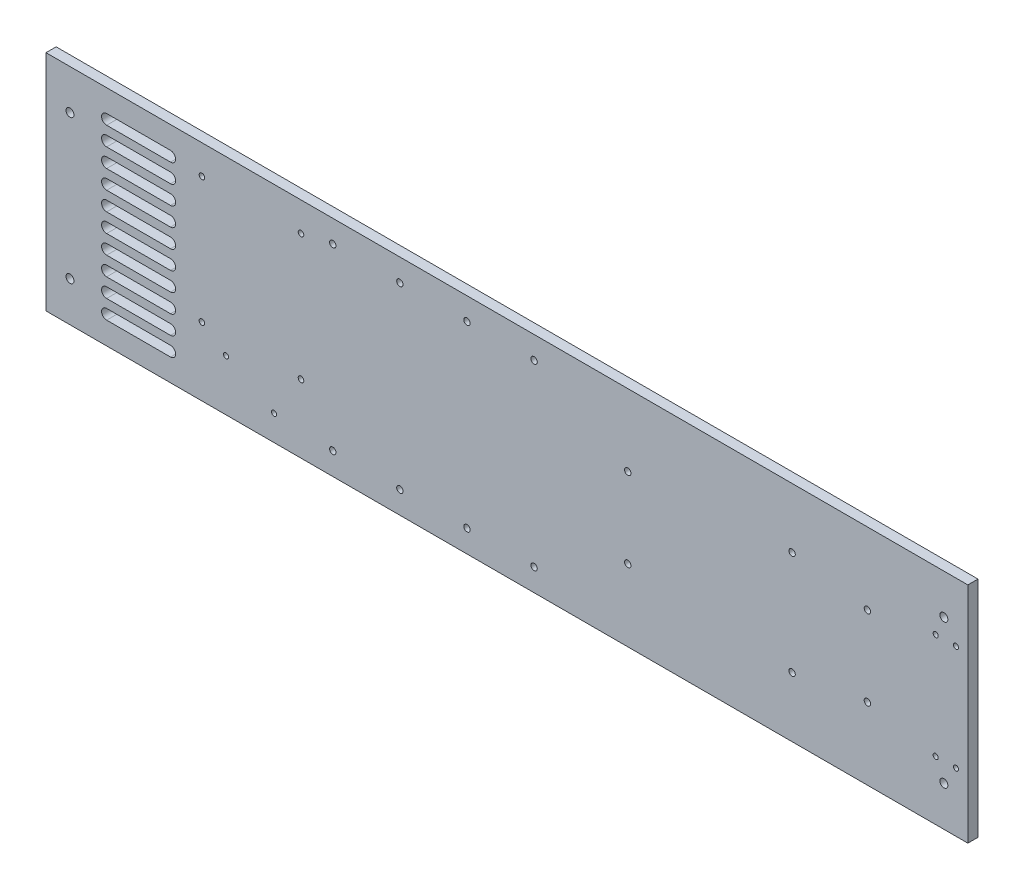
SolidWorks part; units mm, degrees
ref_plane "Front Plane" through (0, 0, 0) normal (0, 0, 1) x (1, 0, 0)
ref_plane "Top Plane" through (0, 0, 0) normal (0, 1, 0) x (1, 0, 0)
ref_plane "Right Plane" through (0, 0, 0) normal (1, 0, 0) x (0, 0, -1)
sketch "Sketch1" plane through (0, 0, 0) normal (0, 0, 1) x (1, 0, 0)
  line L1 (-288.5, 70) -> (288.5, 70)
  line L2 (-288.5, 70) -> (-288.5, -70)
  line L3 (-288.5, -70) -> (288.5, -70)
  line L4 (288.5, 70) -> (288.5, -70)
  line L5 (-288.5, 70) -> (288.5, -70) construction
  line L6 (-288.5, -70) -> (288.5, 70) construction
  point P0 (0, 0)
  dimension "D1" = 577
  dimension "D2" = 140
extrude "Boss-Extrude1" add sketch "Sketch1" along normal blind 6.35
sketch "Sketch2" plane through (0, 0, 6.35) normal (0, 0, 1) x (1, 0, 0)
  line L0 (43.12, 57.5) -> (43.12, -57.5) construction
  line L1 (43.12, -57.5) -> (258.12, -57.5) construction
  line L2 (258.12, -57.5) -> (258.12, 57.5) construction
  line L3 (258.12, 57.5) -> (43.12, 57.5) construction
  line L4 (150.62, 57.5) -> (150.62, -57.5) construction
  line L5 (150.62, -57.5) -> (150.62, 0) construction
  line L6 (150.62, 0) -> (43.12, 0) construction
  line L7 (43.12, 0) -> (258.12, 0) construction
  line L8 (4.9962, 58) -> (38.9962, 58) construction
  line L9 (38.9962, 58) -> (38.9962, -58) construction
  line L10 (38.9962, -58) -> (4.9962, -58) construction
  line L11 (4.9962, -58) -> (4.9962, 58) construction
  line L12 (16.9962, 58) -> (16.9962, -58) construction
  line L13 (38.9962, 0) -> (4.9962, 0) construction
  line L14 (-37.0038, 58) -> (-3.0038, 58) construction
  line L15 (-3.0038, 58) -> (-3.0038, -58) construction
  line L16 (-3.0038, -58) -> (-37.0038, -58) construction
  line L17 (-37.0038, -58) -> (-37.0038, 58) construction
  line L18 (-25.0038, 58) -> (-25.0038, -58) construction
  line L19 (-3.0038, 0) -> (-37.0038, 0) construction
  line L20 (-79.0038, 58) -> (-45.0038, 58) construction
  line L21 (-45.0038, 58) -> (-45.0038, -58) construction
  line L22 (-45.0038, -58) -> (-79.0038, -58) construction
  line L23 (-79.0038, -58) -> (-79.0038, 58) construction
  line L24 (-67.0038, 58) -> (-67.0038, -58) construction
  line L25 (-45.0038, 0) -> (-79.0038, 0) construction
  line L26 (-121.0038, 58) -> (-87.0038, 58) construction
  line L27 (-87.0038, 58) -> (-87.0038, -58) construction
  line L28 (-87.0038, -58) -> (-121.0038, -58) construction
  line L29 (-121.0038, -58) -> (-121.0038, 58) construction
  line L30 (-109.0038, 58) -> (-109.0038, -58) construction
  line L31 (-87.0038, 0) -> (-121.0038, 0) construction
  line L32 (-189.1559, 12.2683) -> (-130.6237, 12.2683) construction
  line L33 (-130.6237, 12.2683) -> (-159.8898, 12.2683) construction
  line L34 (-159.8898, 12.2683) -> (-159.8898, 43.5) construction
  line L35 (-159.8898, 43.5) -> (-159.8898, -43.5) construction
  line L36 (-194.8898, 55.7683) -> (-194.8898, -31.2317) construction
  line L37 (-194.8898, -31.2317) -> (-124.8898, -31.2317) construction
  line L38 (-124.8898, -31.2317) -> (-124.8898, 55.7683) construction
  line L39 (-124.8898, 55.7683) -> (-194.8898, 55.7683) construction
  line L40 (266.2213, 35.125) -> (266.2213, -35.125) construction
  line L41 (266.2213, -35.125) -> (283.2213, -35.125) construction
  line L42 (283.2213, -35.125) -> (283.2213, 35.125) construction
  line L43 (283.2213, 35.125) -> (266.2213, 35.125) construction
  line L44 (274.7213, 35.125) -> (274.7213, -35.125) construction
  line L45 (274.7213, -35.125) -> (274.7213, 0) construction
  line L46 (274.7213, 0) -> (283.2213, 0) construction
  line L47 (283.2213, 0) -> (266.2213, 0) construction
  line L48 (-182.4288, -35.379) -> (-139.1788, -35.379) construction
  line L49 (-139.1788, -35.379) -> (-139.1788, -56.629) construction
  line L50 (-139.1788, -56.629) -> (-182.4288, -56.629) construction
  line L51 (-182.4288, -56.629) -> (-182.4288, -35.379) construction
  line L52 (141.4817, 37) -> (215.4817, 37) construction
  line L53 (215.4817, 37) -> (215.4817, -37) construction
  line L54 (215.4817, -37) -> (141.4817, -37) construction
  line L55 (141.4817, -37) -> (141.4817, 37) construction
  line L56 (141.4817, 0) -> (215.4817, 0) construction
  line L57 (178.4817, 37) -> (178.4817, -37) construction
  circle A0 centre (75.62, 25) radius 2
  circle A1 centre (225.62, 25) radius 2
  circle A2 centre (225.62, -25) radius 2
  circle A3 centre (75.62, -25) radius 2
  circle A4 centre (16.9962, 56) radius 2
  circle A5 centre (16.9962, -56) radius 2
  circle A6 centre (-25.0038, 56) radius 2
  circle A7 centre (-25.0038, -56) radius 2
  circle A8 centre (-67.0038, 56) radius 2
  circle A9 centre (-67.0038, -56) radius 2
  circle A10 centre (-109.0038, 56) radius 2
  circle A11 centre (-109.0038, -56) radius 2
  circle A12 centre (-128.8898, 51.7683) radius 1.75
  circle A13 centre (-190.8898, 51.7683) radius 1.75
  circle A14 centre (-128.8898, -27.2317) radius 1.75
  circle A15 centre (-190.8898, -27.2317) radius 1.75
  circle A16 centre (268.3713, 33) radius 1.6
  circle A17 centre (281.0713, 33) radius 1.6
  circle A18 centre (281.0713, -33) radius 1.6
  circle A19 centre (268.3713, -33) radius 1.6
  circle A20 centre (-145.7788, -54.079) radius 1.5875
  circle A21 centre (-175.8288, -37.929) radius 1.5875
  circle A22 centre (178.4817, 32.5) radius 2
  circle A23 centre (178.4817, -32.5) radius 2
  point P19 (38.9962, 0)
  dimension "D3" = 75
  dimension "D4" = 4
  dimension "D5" = 25
  dimension "D6" = 34
  dimension "D9" = 4
  dimension "D10" = 56
  dimension "D12" = 3.5
  dimension "D13" = 39.5
  dimension "D14" = 31
  dimension "D15" = 4
  dimension "D17" = 4
  dimension "D18" = 4
  dimension "D21" = 3.2
  dimension "D22" = 6.35
  dimension "D23" = 33
  dimension "D27" = 3.175
  dimension "D28" = 3.175
  dimension "D29" = 2.55
  dimension "D30" = 2.55
  dimension "D31" = 6.6
  dimension "D32" = 6.6
  dimension "D35" = 32.5
  dimension "D36" = 4
  dimension "D1" = 215
  dimension "D2" = 115
  dimension "D7" = 116
  dimension "D8" = 22
  dimension "D16" = 4
  dimension "D19" = 70.25
  dimension "D20" = 17
  dimension "D24" = 8
  dimension "D25" = 43.25
  dimension "D26" = 21.25
  dimension "D33" = 74
  dimension "D34" = 74
  dimension "D11" = 4
extrude "Cut-Extrude1" cut sketch "Sketch2" against normal through all
sketch "Sketch4" plane through (0, 0, 6.35) normal (0, 0, 1) x (1, 0, 0)
  line L0 (288.5, 70) -> (-288.5, 70) construction
  line L1 (-288.5, 70) -> (-288.5, -70) construction
  line L2 (-73.8138, 0) -> (0, 0) construction
  line L3 (0, 0) -> (0, 94.1959) construction
  circle A0 centre (-273.5, 45) radius 2.5
  circle A1 centre (273.5, 45) radius 2.5
  circle A2 centre (273.5, -45) radius 2.5
  circle A3 centre (-273.5, -45) radius 2.5
  dimension "D1" = 5
  dimension "D2" = 25
  dimension "D3" = 15
extrude "Cut-Extrude2" cut sketch "Sketch4" against normal through all
sketch "Sketch5" plane through (0, 0, 6.35) normal (0, 0, 1) x (1, 0, 0)
  line L0 (-250.5462, 52.825) -> (-210.5462, 52.825) construction
  line L1 (-250.5462, 56) -> (-210.5462, 56)
  line L2 (-250.5462, 49.65) -> (-210.5462, 49.65)
  line L3 (-250.5462, 41.0861) -> (-210.5462, 41.0861) construction
  line L4 (-250.5462, 44.2611) -> (-210.5462, 44.2611)
  line L5 (-250.5462, 37.9111) -> (-210.5462, 37.9111)
  line L6 (-250.5462, 29.3472) -> (-210.5462, 29.3472) construction
  line L7 (-250.5462, 32.5222) -> (-210.5462, 32.5222)
  line L8 (-250.5462, 26.1722) -> (-210.5462, 26.1722)
  line L9 (-250.5462, 17.6083) -> (-210.5462, 17.6083) construction
  line L10 (-250.5462, 20.7833) -> (-210.5462, 20.7833)
  line L11 (-250.5462, 14.4333) -> (-210.5462, 14.4333)
  line L12 (-250.5462, 5.8694) -> (-210.5462, 5.8694) construction
  line L13 (-250.5462, 9.0444) -> (-210.5462, 9.0444)
  line L14 (-250.5462, 2.6944) -> (-210.5462, 2.6944)
  line L15 (-250.5462, -5.8694) -> (-210.5462, -5.8694) construction
  line L16 (-250.5462, -2.6944) -> (-210.5462, -2.6944)
  line L17 (-250.5462, -9.0444) -> (-210.5462, -9.0444)
  line L18 (-250.5462, -17.6083) -> (-210.5462, -17.6083) construction
  line L19 (-250.5462, -14.4333) -> (-210.5462, -14.4333)
  line L20 (-250.5462, -20.7833) -> (-210.5462, -20.7833)
  line L21 (-250.5462, -29.3472) -> (-210.5462, -29.3472) construction
  line L22 (-250.5462, -26.1722) -> (-210.5462, -26.1722)
  line L23 (-250.5462, -32.5222) -> (-210.5462, -32.5222)
  line L24 (-250.5462, -41.0861) -> (-210.5462, -41.0861) construction
  line L25 (-250.5462, -37.9111) -> (-210.5462, -37.9111)
  line L26 (-250.5462, -44.2611) -> (-210.5462, -44.2611)
  line L27 (-250.5462, -52.825) -> (-210.5462, -52.825) construction
  line L28 (-250.5462, -49.65) -> (-210.5462, -49.65)
  line L29 (-250.5462, -56) -> (-210.5462, -56)
  line L30 (288.5, 70) -> (-288.5, 70) construction
  line L31 (-288.5, -70) -> (288.5, -70) construction
  arc A0 (-250.5462, 56) -> (-250.5462, 49.65) centre (-250.5462, 52.825) ccw
  arc A1 (-210.5462, 49.65) -> (-210.5462, 56) centre (-210.5462, 52.825) ccw
  arc A2 (-250.5462, 44.2611) -> (-250.5462, 37.9111) centre (-250.5462, 41.0861) ccw
  arc A3 (-210.5462, 37.9111) -> (-210.5462, 44.2611) centre (-210.5462, 41.0861) ccw
  arc A4 (-250.5462, 32.5222) -> (-250.5462, 26.1722) centre (-250.5462, 29.3472) ccw
  arc A5 (-210.5462, 26.1722) -> (-210.5462, 32.5222) centre (-210.5462, 29.3472) ccw
  arc A6 (-250.5462, 20.7833) -> (-250.5462, 14.4333) centre (-250.5462, 17.6083) ccw
  arc A7 (-210.5462, 14.4333) -> (-210.5462, 20.7833) centre (-210.5462, 17.6083) ccw
  arc A8 (-250.5462, 9.0444) -> (-250.5462, 2.6944) centre (-250.5462, 5.8694) ccw
  arc A9 (-210.5462, 2.6944) -> (-210.5462, 9.0444) centre (-210.5462, 5.8694) ccw
  arc A10 (-250.5462, -2.6944) -> (-250.5462, -9.0444) centre (-250.5462, -5.8694) ccw
  arc A11 (-210.5462, -9.0444) -> (-210.5462, -2.6944) centre (-210.5462, -5.8694) ccw
  arc A12 (-250.5462, -14.4333) -> (-250.5462, -20.7833) centre (-250.5462, -17.6083) ccw
  arc A13 (-210.5462, -20.7833) -> (-210.5462, -14.4333) centre (-210.5462, -17.6083) ccw
  arc A14 (-250.5462, -26.1722) -> (-250.5462, -32.5222) centre (-250.5462, -29.3472) ccw
  arc A15 (-210.5462, -32.5222) -> (-210.5462, -26.1722) centre (-210.5462, -29.3472) ccw
  arc A16 (-250.5462, -37.9111) -> (-250.5462, -44.2611) centre (-250.5462, -41.0861) ccw
  arc A17 (-210.5462, -44.2611) -> (-210.5462, -37.9111) centre (-210.5462, -41.0861) ccw
  arc A18 (-250.5462, -49.65) -> (-250.5462, -56) centre (-250.5462, -52.825) ccw
  arc A19 (-210.5462, -56) -> (-210.5462, -49.65) centre (-210.5462, -52.825) ccw
  point P2 (-230.5462, 52.825)
  point P10 (-230.5462, 41.0861)
  point P17 (-230.5462, 29.3472)
  point P24 (-230.5462, 17.6083)
  point P31 (-230.5462, 5.8694)
  point P38 (-230.5462, -5.8694)
  point P45 (-230.5462, -17.6083)
  point P52 (-230.5462, -29.3472)
  point P59 (-230.5462, -41.0861)
  point P66 (-230.5462, -52.825)
  dimension "D1" = 3.175
  dimension "D2" = 40
  dimension "D4" = 14
  dimension "D5" = 14
  dimension "D3" = 10
extrude "Cut-Extrude3" cut sketch "Sketch5" against normal through all
